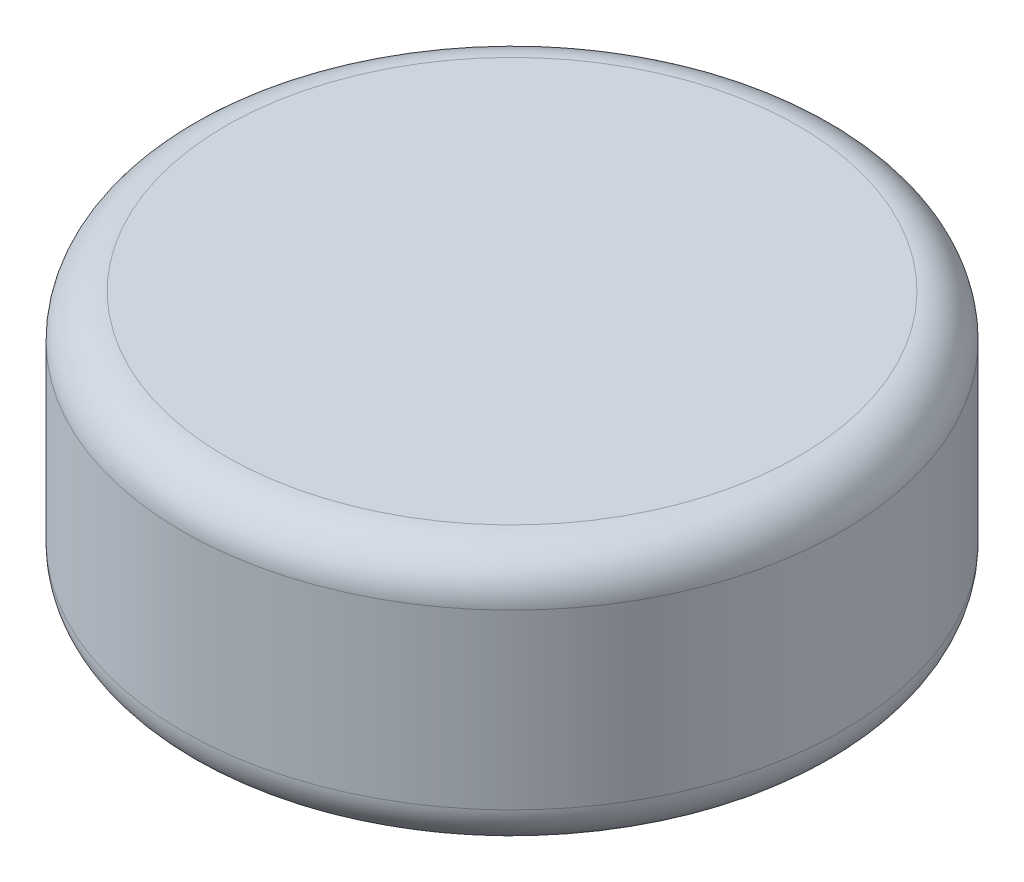
SolidWorks part; units mm, degrees
ref_plane "Front Plane" through (0, 0, 0) normal (0, 0, 1) x (1, 0, 0)
ref_plane "Top Plane" through (0, 0, 0) normal (0, 1, 0) x (1, 0, 0)
ref_plane "Right Plane" through (0, 0, 0) normal (1, 0, 0) x (0, 0, -1)
sketch "Sketch1" plane through (0, 0, 0) normal (0, 1, 0) x (1, 0, 0)
  circle A0 centre (0, 0) radius 76.2
  dimension "D1" = 152.4
extrude "Boss-Extrude1" add sketch "Sketch1" along normal blind 60
fillet "Fillet3" radius 10 2 edges at (0, 0, 76.2) (0, 60, 76.2)
